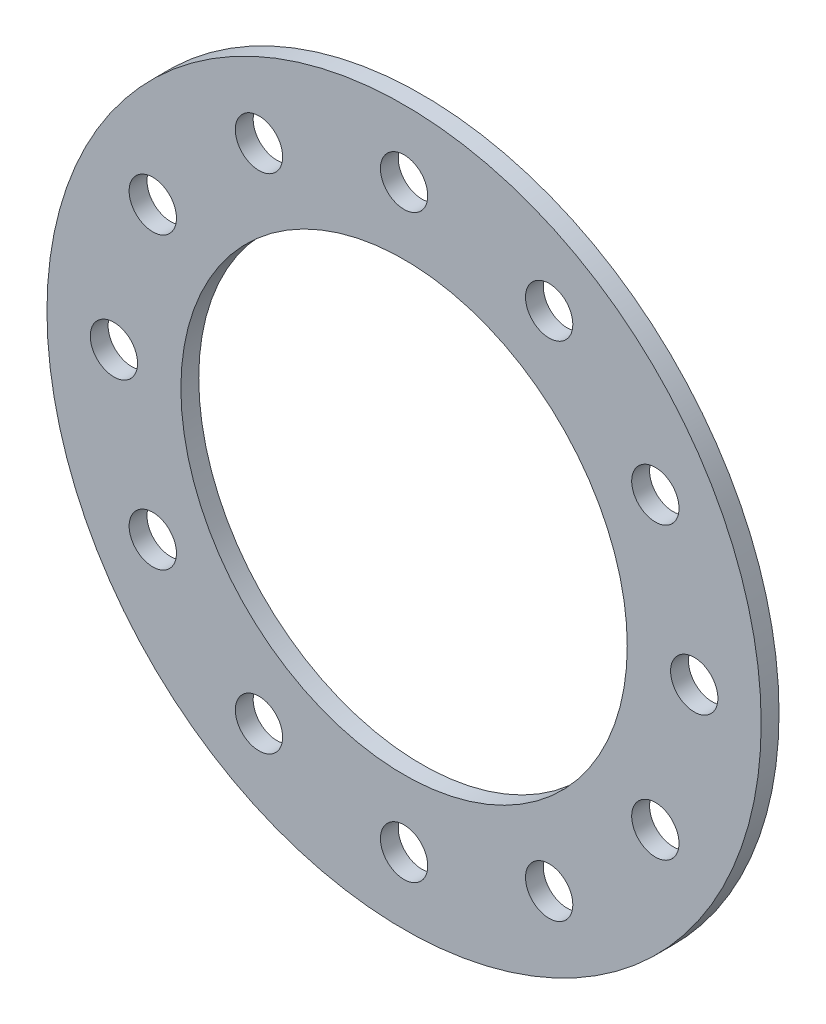
SolidWorks part; units mm, degrees
ref_plane "Front" through (0, 0, 0) normal (0, 0, 1) x (1, 0, 0)
ref_plane "Top" through (0, 0, 0) normal (0, 1, 0) x (1, 0, 0)
ref_plane "Right" through (0, 0, 0) normal (1, 0, 0) x (0, 0, -1)
sketch "Sketch1" plane through (0, 0, 0) normal (0, 0, 1) x (1, 0, 0)
  circle A0 centre (0, 0) radius 40
  circle A1 centre (0, 0) radius 25
  dimension "D1" = 50
  dimension "D2" = 80
extrude "Boss-Extrude1" add sketch "Sketch1" along normal blind 2
hole_wizard "M5 Clearance Hole1" positions "Sketch2" profile "Sketch3" hole size "M5" standard "ANSI Metric" end condition through all
sketch "Sketch2" plane through (0, 0, 2) normal (0, 0, 1) x (1, 0, 0)
  line L0 (0, 0) -> (0, 32.5) construction
  circle A0 centre (0, 0) radius 32.5
  point P0 (0, 32.5)
  dimension "D1" = 65
sketch "Sketch3" plane through (0, 32.5, 2) normal (1, 0, 0) x (0, -1, 0)
  line L0 (0, 0) -> (0, 2)
  line L1 (0, 2) -> (2.65, 2)
  line L2 (2.65, 2) -> (2.65, 0)
  line L5 (2.65, 0) -> (0, 0)
  line L11 (0, -6.35) -> (0, 107.95) construction
  dimension "Thru Hole Dia." = 5.3
  dimension "Thru Hole Depth" = 2
pattern_circular "CirPattern1" count 12 over 360 about axis through (0, 0, 0) along (0, 0, 1) of "M5 Clearance Hole1"
